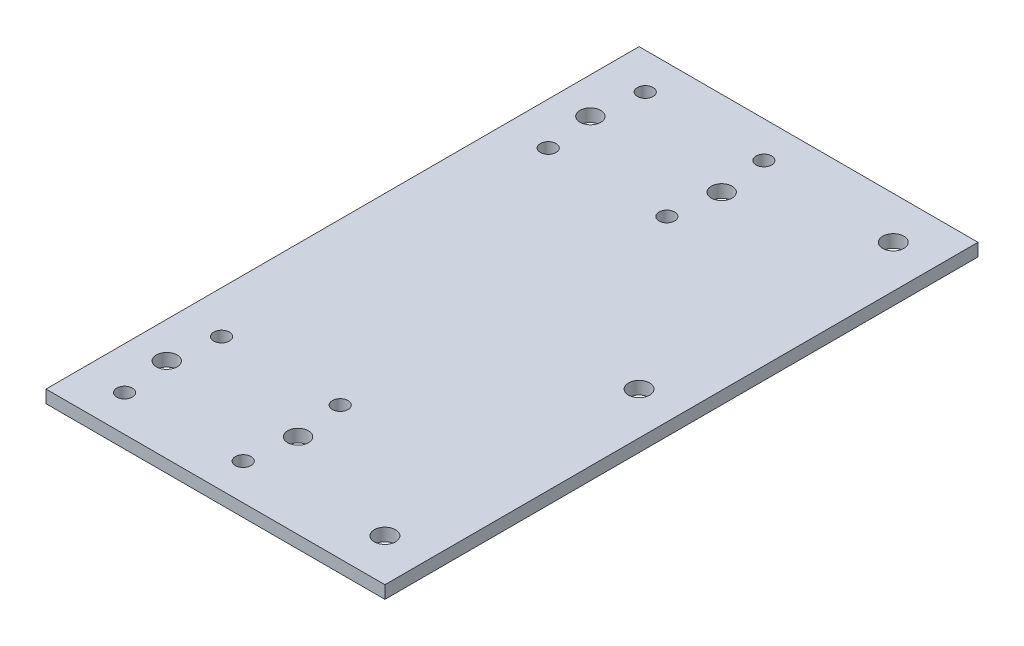
SolidWorks part; units mm, degrees
ref_plane "前视基准面" through (0, 0, 0) normal (0, 0, 1) x (1, 0, 0)
ref_plane "上视基准面" through (0, 0, 0) normal (0, 1, 0) x (1, 0, 0)
ref_plane "右视基准面" through (0, 0, 0) normal (1, 0, 0) x (0, 0, -1)
other "Configuration Table"
sketch "草图1" plane through (0, 0, 0) normal (0, 1, 0) x (1, 0, 0)
  line L0 (-40, 0) -> (49960, 0) construction
  line L1 (-40, -70) -> (40, -70)
  line L2 (-40, -70) -> (-40, 70)
  line L3 (-40, 70) -> (40, 70)
  line L4 (40, -70) -> (40, 70)
  line L5 (-40, -70) -> (40, 70) construction
  line L6 (-40, 70) -> (40, -70) construction
  line L7 (-40, 70) -> (8, 70)
  line L8 (-40, 70) -> (-40, 30)
  line L9 (-40, 30) -> (8, 30)
  line L10 (8, 70) -> (8, 30)
  line L11 (-40, -70) -> (8, -70)
  line L12 (-40, -70) -> (-40, -30)
  line L13 (-40, -30) -> (8, -30)
  line L14 (8, -70) -> (8, -30)
  line L15 (-40, 70) -> (-30, 70)
  line L16 (-40, 70) -> (-40, 61.45)
  line L17 (-40, 61.45) -> (-30, 61.45)
  line L18 (-30, 70) -> (-30, 61.45)
  line L19 (-16, 30) -> (-16, 50030) construction
  line L20 (8, 50) -> (-0.5, 50) construction
  line L22 (40, 70) -> (30, 70)
  line L23 (40, 70) -> (40, 60)
  line L24 (40, 60) -> (30, 60)
  line L25 (30, 70) -> (30, 60)
  circle A0 centre (-30, 61.45) radius 1.85
  circle A1 centre (-2, 61.45) radius 1.85
  circle A2 centre (-2, 38.55) radius 1.85
  circle A3 centre (-30, 38.55) radius 1.85
  circle A4 centre (-0.5, 50) radius 2.45
  circle A5 centre (-31.5, 50) radius 2.45
  circle A6 centre (-2, -38.55) radius 1.85
  circle A7 centre (-0.5, -50) radius 2.45
  circle A8 centre (-2, -61.45) radius 1.85
  circle A9 centre (-30, -38.55) radius 1.85
  circle A10 centre (-31.5, -50) radius 2.45
  circle A11 centre (-30, -61.45) radius 1.85
  circle A12 centre (30, 60) radius 2.5
  circle A13 centre (30, 0) radius 2.5
  circle A14 centre (30, -60) radius 2.5
  point P0 (0, 0)
  point P18 (8, 50)
  point P21 (-16, 30)
  point P33 (-40, 0)
  dimension "D9" = 3.7
  dimension "D11" = 4.9
  dimension "D14" = 5
  dimension "D1" = 80
  dimension "D2" = 140
  dimension "D3" = 40
  dimension "D4" = 48
  dimension "D5" = 48
  dimension "D6" = 40
  dimension "D7" = 10
  dimension "D8" = 8.55
  dimension "D10" = 8.5
  dimension "D12" = 10
  dimension "D13" = 10
  dimension "D15" = 3
extrude "凸台-拉伸1" add sketch "草图1" along normal blind 3 contours A12 L25 L3 L10 L9 L2 L13 L14 L1 L4 L24 A14 A13 | A12 L24 L4 L3 L25 | A0 L17 L2 L9 L10 L7 L18 A3 A2 A1 A4 A5 | A0 L18 L3 L8 L17 | L1 L14 L13 L2 A7 A6 A8 A9 A10 A11
